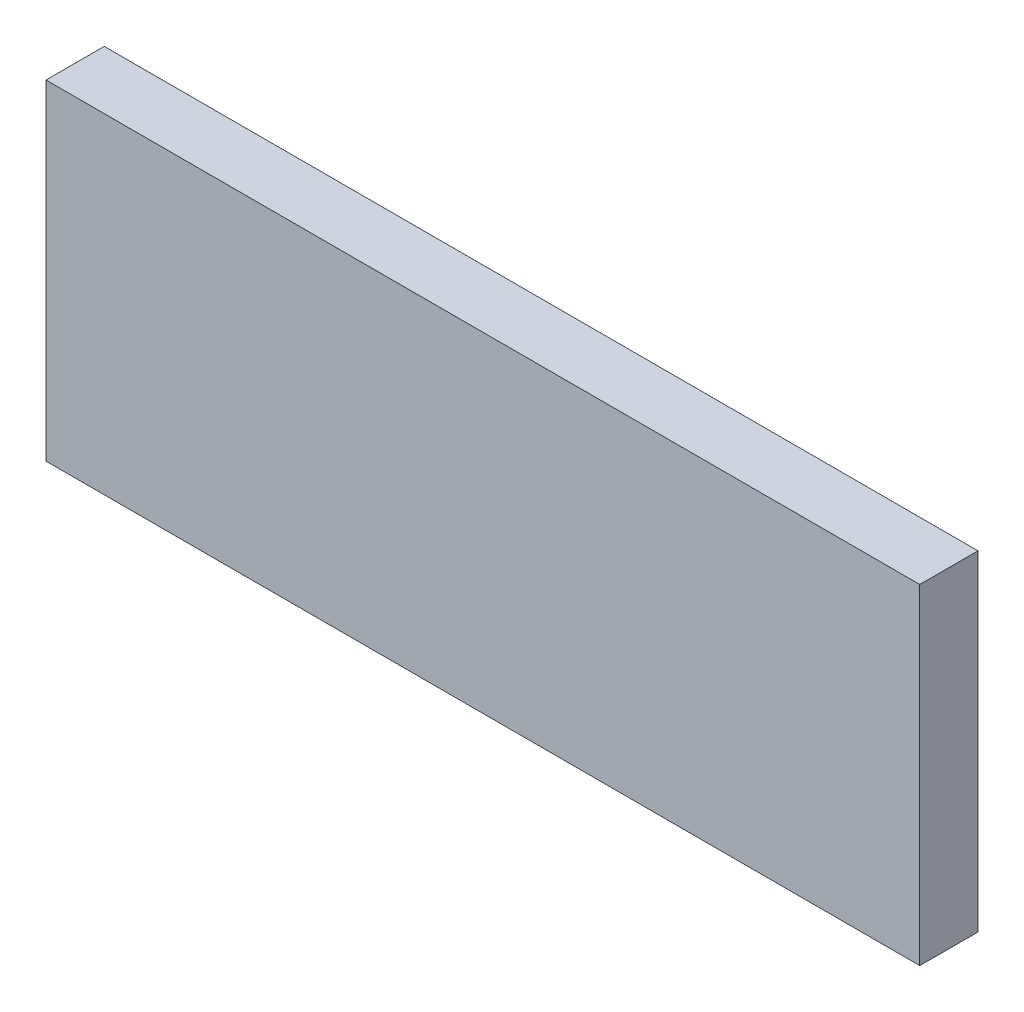
SolidWorks part; units mm, degrees
material "Alumina"
ref_plane "Front Plane" through (0, 0, 0) normal (0, 0, 1) x (1, 0, 0)
ref_plane "Top Plane" through (0, 0, 0) normal (0, 1, 0) x (1, 0, 0)
ref_plane "Right Plane" through (0, 0, 0) normal (1, 0, 0) x (0, 0, -1)
sketch "Sketch2" plane through (0, 0, 0) normal (0, 0, 1) x (1, 0, 0)
  line L1 (0, 0) -> (4500, 0)
  line L2 (0, 0) -> (0, 1700)
  line L3 (0, 1700) -> (4500, 1700)
  line L4 (4500, 0) -> (4500, 1700)
  dimension "Width" = 1700
  dimension "Length" = 4500
extrude "Boss-Extrude1" add sketch "Sketch2" along normal blind 300
shell "Shell1" thickness 50
